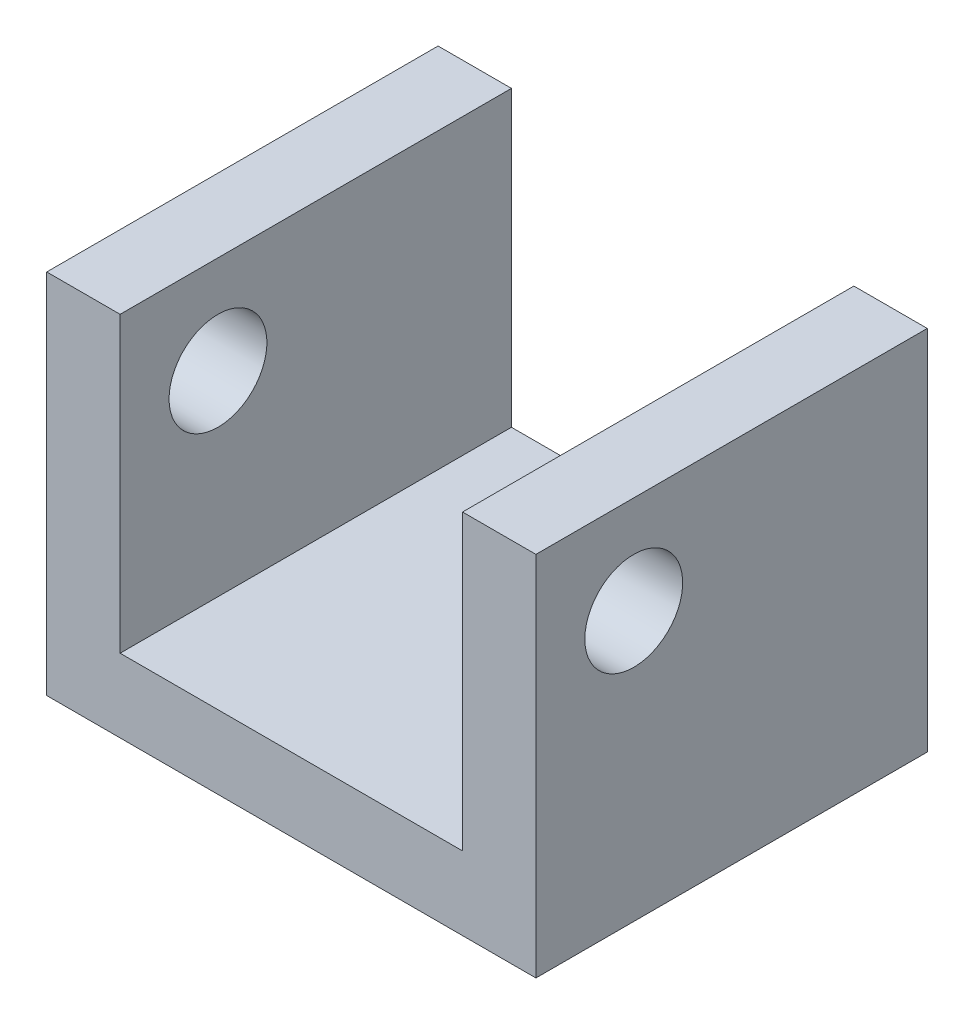
SolidWorks part; units mm, degrees
ref_plane "Front Plane" through (0, 0, 0) normal (0, 0, 1) x (1, 0, 0)
ref_plane "Top Plane" through (0, 0, 0) normal (0, 1, 0) x (1, 0, 0)
ref_plane "Right Plane" through (0, 0, 0) normal (1, 0, 0) x (0, 0, -1)
sketch "Sketch1" plane through (0, 0, 0) normal (0, 1, 0) x (1, 0, 0)
  line L1 (-5, -4) -> (5, -4)
  line L2 (-5, -4) -> (-5, 4)
  line L3 (-5, 4) -> (5, 4)
  line L4 (5, -4) -> (5, 4)
  line L5 (-5, -4) -> (5, 4) construction
  line L6 (-5, 4) -> (5, -4) construction
  point P0 (0, 0)
  dimension "D1" = 10
  dimension "D2" = 8
extrude "Boss-Extrude1" add sketch "Sketch1" along normal blind 1.5
sketch "Sketch3" plane through (0, 1.5, 0) normal (0, 1, 0) x (1, 0, 0)
  line L0 (-5, -4) -> (5, -4) construction
  line L1 (-5, 4) -> (-3.5, 4)
  line L2 (-5, 4) -> (-5, -4)
  line L3 (-5, -4) -> (-3.5, -4)
  line L4 (-3.5, 4) -> (-3.5, -4)
  line L5 (0, 4) -> (0, -4) construction
  line L6 (3.5, 4) -> (3.5, -4)
  line L7 (5, -4) -> (3.5, -4)
  line L8 (5, 4) -> (5, -4)
  line L9 (5, 4) -> (3.5, 4)
  point P11 (0, 0)
  dimension "D1" = 1.5
extrude "Boss-Extrude2" add sketch "Sketch3" along normal blind 6
sketch "Sketch4" plane through (0, 1.5, 0) normal (0, 1, 0) x (1, 0, 0)
  circle A0 centre (0, 1.7347) radius 1.85 construction
  circle A1 centre (0, 1.7347) radius 1.85 construction
  circle A2 centre (0, 1.7347) radius 1.2
  dimension "D1" = 2.4
extrude "Cut-Extrude1" cut sketch "Sketch4" against normal through all
sketch "Sketch5" plane through (-5, 0, 0) normal (-1, 0, 0) x (0, 0, 1)
  line L0 (4, 5.5) -> (-4, 5.5) construction
  line L1 (4, 7.5) -> (4, 0) construction
  line L2 (-4, 7.5) -> (-4, 0) construction
  line L3 (2, 7.5) -> (2, 5.5) construction
  line L4 (-4, 7.5) -> (4, 7.5) construction
  circle A0 centre (2, 5.5) radius 1
  point P12 (0, 0)
  dimension "D3" = 2
  dimension "D1" = 2
  dimension "D2" = 2
extrude "Cut-Extrude2" cut sketch "Sketch5" against normal through all
